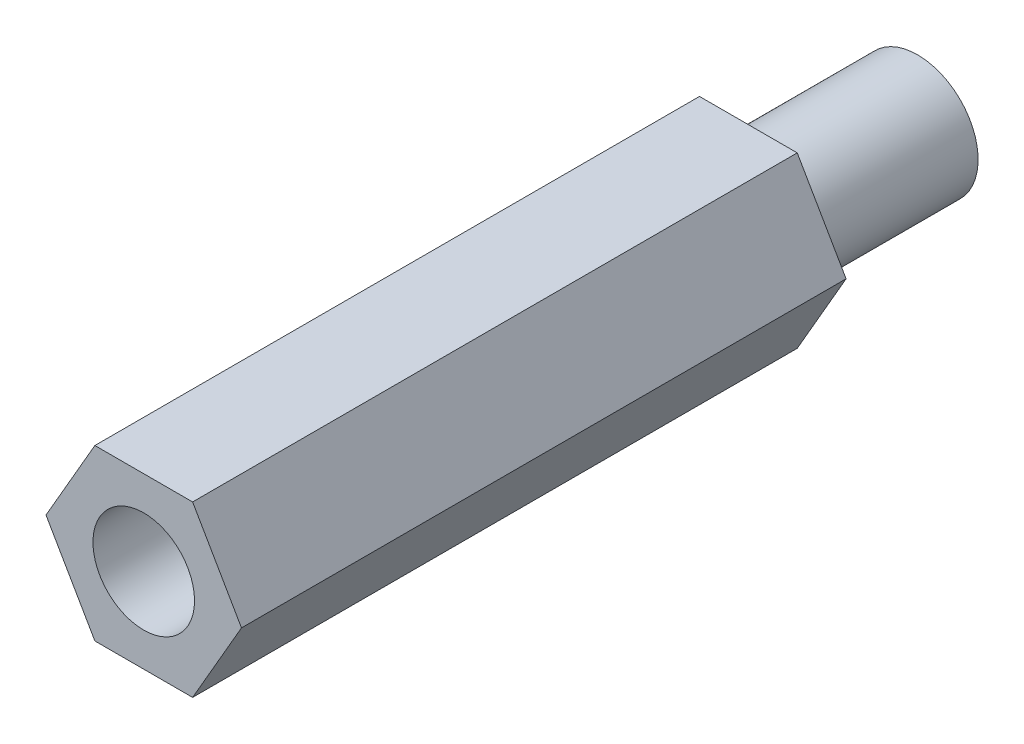
SolidWorks part; units mm, degrees
material "黃銅"
ref_plane "前基準面" through (0, 0, 0) normal (0, 0, 1) x (1, 0, 0)
ref_plane "上基準面" through (0, 0, 0) normal (0, 1, 0) x (1, 0, 0)
ref_plane "右基準面" through (0, 0, 0) normal (1, 0, 0) x (0, 0, -1)
sketch "草圖1" plane through (0, 0, 0) normal (0, 0, 1) x (1, 0, 0)
  line L1 (-2.0207, 3.5) -> (-4.0415, 0)
  line L2 (-4.0415, 0) -> (-2.0207, -3.5)
  line L3 (-2.0207, -3.5) -> (2.0207, -3.5)
  line L4 (2.0207, -3.5) -> (4.0415, 0)
  line L5 (4.0415, 0) -> (2.0207, 3.5)
  line L6 (2.0207, 3.5) -> (-2.0207, 3.5)
  circle A0 centre (0, 0) radius 3.5 construction
  dimension "D1" = 7
extrude "填料-伸長1" add sketch "草圖1" along normal blind 25
sketch "草圖4" plane through (0, 0, 0) normal (0, 0, -1) x (-1, 0, 0)
  circle A0 centre (0, 0) radius 2.5
  dimension "D1" = 5
extrude "填料-伸長2" add sketch "草圖4" along normal blind 7
hole_wizard "M5x0.8 Tapped Hole1" positions "草圖2" profile "草圖3" tap size "M5x0.8" standard "ANSI Metric"
sketch "草圖2" plane through (0, 0, 25) normal (0, 0, 1) x (1, 0, 0)
  point P0 (0, 0)
sketch "草圖3" plane through (0, 0, 25) normal (1, 0, 0) x (0, -1, 0)
  line L0 (0, 0) -> (0, 15.2618)
  line L1 (0, 15.2618) -> (2.1, 14)
  line L2 (2.1, 14) -> (2.1, 0)
  line L5 (2.1, 0) -> (0, 0)
  line L10 (0, 15.2618) -> (-2.1, 14) construction
  line L11 (0, -6.35) -> (0, 107.95) construction
  dimension "螺孔鑽直徑" = 4.2
  dimension "螺孔鑽深度" = 14
  dimension "導頭角度" = 118
